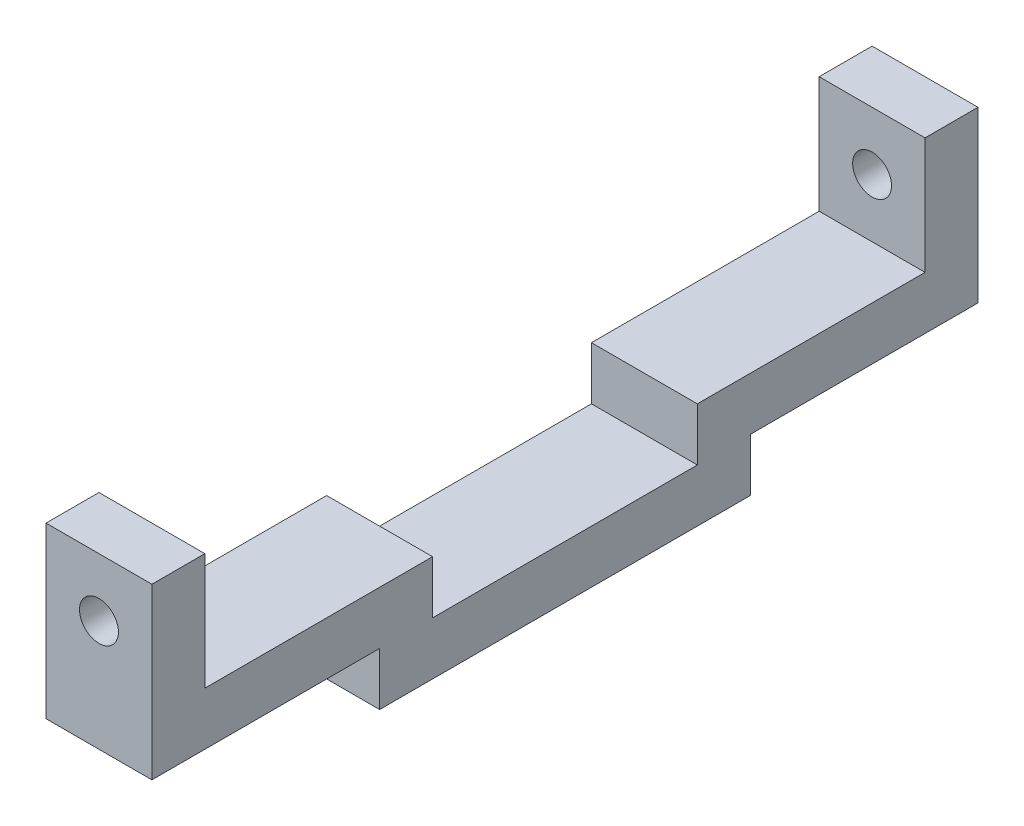
SolidWorks part; units mm, degrees
ref_plane "Front Plane" through (0, 0, 0) normal (0, 0, 1) x (1, 0, 0)
ref_plane "Top Plane" through (0, 0, 0) normal (0, 1, 0) x (1, 0, 0)
ref_plane "Right Plane" through (0, 0, 0) normal (1, 0, 0) x (0, 0, -1)
sketch "Sketch1" plane through (0, 0, 0) normal (1, 0, 0) x (0, 0, -1)
  line L1 (-39, -10.5) -> (39, -10.5)
  line L2 (-39, -10.5) -> (-39, 10.5)
  line L3 (-39, 10.5) -> (39, 10.5)
  line L4 (39, -10.5) -> (39, 10.5)
  line L5 (-39, -10.5) -> (39, 10.5) construction
  line L6 (-39, 10.5) -> (39, -10.5) construction
  line L7 (-34, 10.5) -> (34, 10.5)
  line L8 (-34, 10.5) -> (-34, -5.5)
  line L9 (-34, -5.5) -> (34, -5.5)
  line L10 (34, 10.5) -> (34, -5.5)
  line L11 (12.5, -5.5) -> (-12.5, -5.5)
  line L12 (12.5, -5.5) -> (12.5, -0.5)
  line L13 (12.5, -0.5) -> (-12.5, -0.5)
  line L14 (-12.5, -5.5) -> (-12.5, -0.5)
  line L15 (12.5, -5.5) -> (-12.5, -0.5) construction
  line L16 (12.5, -0.5) -> (-12.5, -5.5) construction
  line L21 (-34, -5.5) -> (-12.5, -5.5)
  line L22 (-34, -5.5) -> (-34, -0.5)
  line L23 (-34, -0.5) -> (-12.5, -0.5)
  line L24 (-12.5, -5.5) -> (-12.5, -0.5)
  line L25 (34, -5.5) -> (12.5, -5.5)
  line L26 (34, -5.5) -> (34, -0.5)
  line L27 (34, -0.5) -> (12.5, -0.5)
  line L28 (12.5, -5.5) -> (12.5, -0.5)
  point P0 (0, 0)
  point P10 (0, -3)
  dimension "D1" = 68
  dimension "D3" = 16
  dimension "D4" = 5
  dimension "D5" = 5
  dimension "D6" = 5
  dimension "D7" = 25
  dimension "D8" = 5
  dimension "D9" = 0
extrude "Boss-Extrude1" add sketch "Sketch1" along normal blind 10 contours L3 L10 L9 L8 L2 L1 L4 | L22 L21 L24 L23 | L26 L25 L28 L27
sketch "Sketch2" plane through (0, 0, -34) normal (0, 0, 1) x (1, 0, 0)
  line L0 (10, 10.5) -> (0, 10.5) construction
  line L2 (10, 10.5) -> (10, -0.5) construction
  circle A0 centre (5, 5) radius 1.8366
  dimension "D1" = 5.5
  dimension "D2" = 5
extrude "Cut-Extrude1" cut sketch "Sketch2" against normal through all and the other way through all contours A0
sketch "Sketch3" plane through (10, 0, 0) normal (1, 0, 0) x (0, 0, -1)
  line L0 (-34, -0.5) -> (-12.5, -0.5) construction
  line L1 (-39, -10.5) -> (-17.5, -10.5)
  line L2 (-39, -10.5) -> (-39, -5.5)
  line L3 (-39, -5.5) -> (-17.5, -5.5)
  line L4 (-17.5, -10.5) -> (-17.5, -5.5)
  line L5 (-12.5, -5.5) -> (-12.5, -0.5) construction
  dimension "D1" = 5
  dimension "D2" = 5
extrude "Cut-Extrude2" cut sketch "Sketch3" against normal blind 10
mirror "Mirror1" about plane through (0, 0, 0) normal (0, 0, 1) of "Cut-Extrude2"
